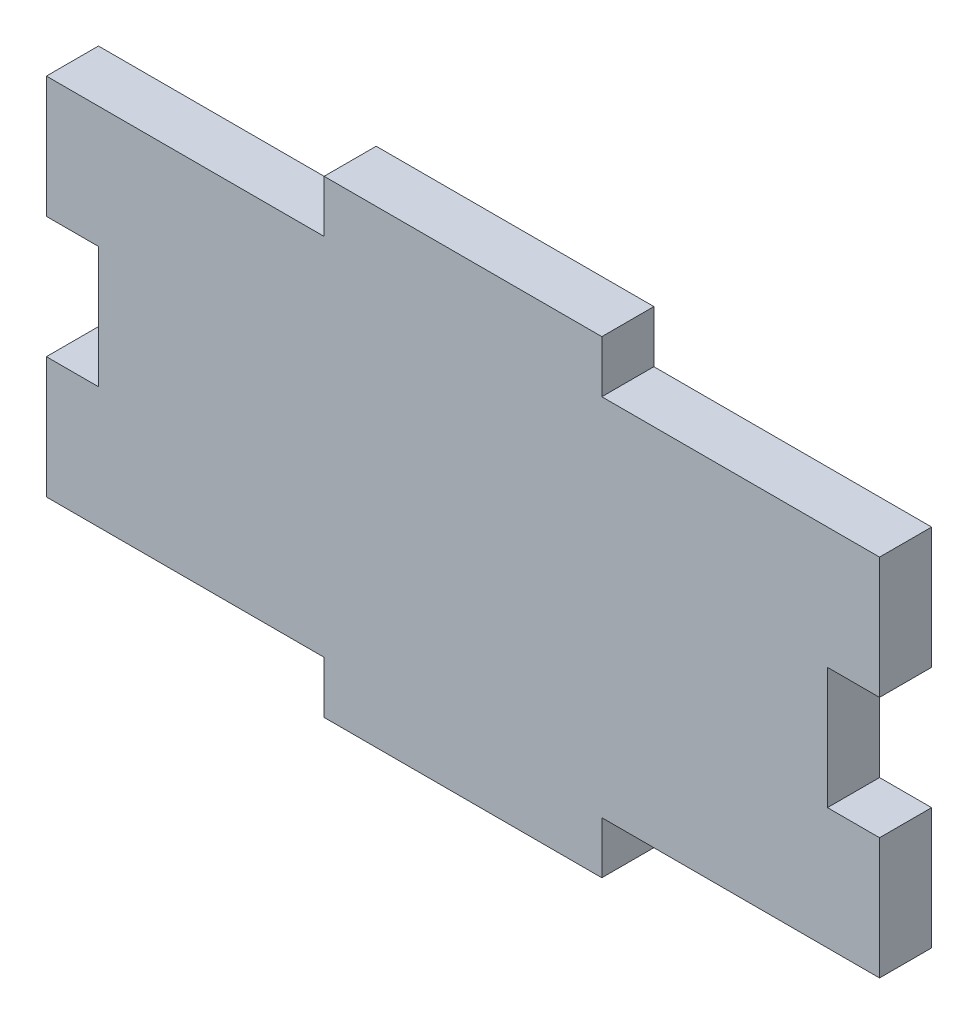
SolidWorks part; units mm, degrees
ref_plane "Front Plane" through (0, 0, 0) normal (0, 0, 1) x (1, 0, 0)
ref_plane "Top Plane" through (0, 0, 0) normal (0, 1, 0) x (1, 0, 0)
ref_plane "Right Plane" through (0, 0, 0) normal (1, 0, 0) x (0, 0, -1)
sketch "Sketch1" plane through (0, 0, 0) normal (0, 0, 1) x (1, 0, 0)
  line L0 (-24, 10.5) -> (-8, 10.5)
  line L1 (-8, 10.5) -> (-8, 13.5)
  line L2 (-8, 13.5) -> (8, 13.5)
  line L3 (8, 13.5) -> (8, 10.5)
  line L4 (8, 10.5) -> (24, 10.5)
  line L5 (24, 10.5) -> (24, 3.5)
  line L6 (24, 3.5) -> (21, 3.5)
  line L7 (21, 3.5) -> (21, -3.5)
  line L8 (21, -3.5) -> (24, -3.5)
  line L9 (24, -3.5) -> (24, -10.5)
  line L10 (55, 0) -> (-55, 0) construction
  line L11 (8, -10.5) -> (24, -10.5)
  line L12 (8, -13.5) -> (8, -10.5)
  line L13 (-8, -13.5) -> (8, -13.5)
  line L14 (-8, -10.5) -> (-8, -13.5)
  line L15 (-24, -10.5) -> (-8, -10.5)
  line L16 (0, -55) -> (0, 55) construction
  line L17 (-24, -3.5) -> (-24, -10.5)
  line L18 (-21, -3.5) -> (-24, -3.5)
  line L19 (-21, 3.5) -> (-21, -3.5)
  line L20 (-24, 3.5) -> (-21, 3.5)
  line L21 (-24, 10.5) -> (-24, 3.5)
  point P8 (0, 13.5)
  point P15 (21, 0)
  dimension "D1" = 16
  dimension "D2" = 21
  dimension "D3" = 3
extrude "Boss-Extrude1" add sketch "Sketch1" along normal blind 3 contours L0 L1 L2 L3 L4 L5 L6 L7 L8 L9 L11 L12 L13 L14 L15 L17 L18 L19 L20 L21
